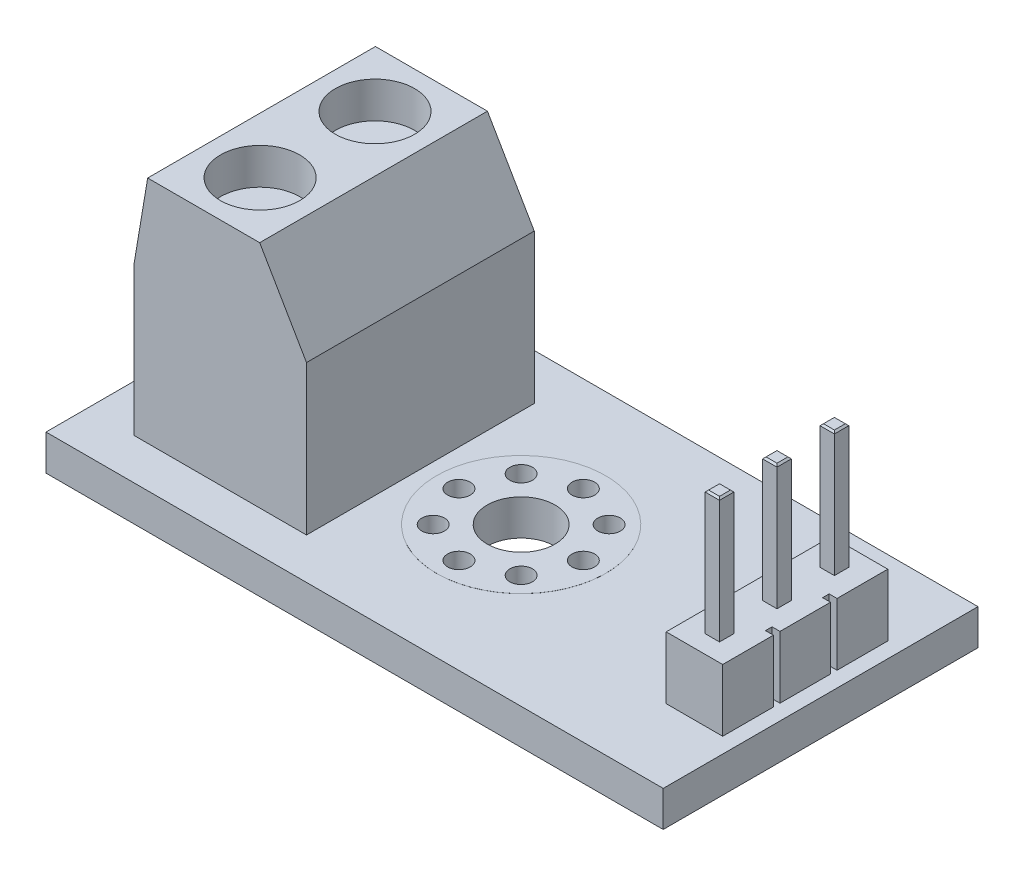
SolidWorks part; units mm, degrees
ref_plane "Front Plane" through (0, 0, 0) normal (0, 0, 1) x (1, 0, 0)
ref_plane "Top Plane" through (0, 0, 0) normal (0, 1, 0) x (1, 0, 0)
ref_plane "Right Plane" through (0, 0, 0) normal (1, 0, 0) x (0, 0, -1)
sketch "Sketch1" plane through (0, 0, 0) normal (0, 1, 0) x (1, 0, 0)
  line L1 (-13.6462, 6.9596) -> (13.6461, 6.9596)
  line L2 (-13.6462, 6.9596) -> (-13.6462, -6.9596)
  line L3 (-13.6462, -6.9596) -> (13.6461, -6.9596)
  line L4 (13.6461, 6.9596) -> (13.6461, -6.9596)
  line L5 (-13.6462, 6.9596) -> (13.6461, -6.9596) construction
  line L6 (-13.6462, -6.9596) -> (13.6461, 6.9596) construction
  point P0 (0, 0)
  dimension "D1" = 13.9192
  dimension "D2" = 27.2923
extrude "Boss-Extrude1" add sketch "Sketch1" along normal mid plane 1.5748
sketch "Sketch2" plane through (0, 0.7874, 0) normal (0, 1, 0) x (1, 0, 0)
  line L0 (-13.6462, 6.9596) -> (-13.6462, -6.9596) construction
  circle A2 centre (0.4038, 0) radius 1.5
  circle A3 centre (0.4038, 2.75) radius 0.5
  circle A5 centre (2.3484, 1.9445) radius 0.5
  circle A6 centre (3.1539, 0) radius 0.5
  circle A7 centre (2.3484, -1.9445) radius 0.5
  circle A8 centre (0.4039, -2.75) radius 0.5
  circle A9 centre (-1.5407, -1.9445) radius 0.5
  circle A10 centre (-2.3461, 0) radius 0.5
  circle A11 centre (-1.5407, 1.9445) radius 0.5
  point P24 (0.4039, 0)
  dimension "D1" = 3
  dimension "D2" = 12.55
  dimension "D3" = 2.75
  dimension "D4" = 1
  dimension "D5" = 8
extrude "Cut-Extrude1" cut sketch "Sketch2" against normal through all
sketch "Sketch3" plane through (0, 0.7874, 0) normal (0, 1, 0) x (1, 0, 0)
  line L0 (13.6461, -6.9596) -> (13.6461, 6.9596) construction
  line L1 (10.4661, 3.65) -> (12.9661, 3.65)
  line L2 (10.4661, 3.65) -> (10.4661, -3.65)
  line L3 (10.4661, -3.65) -> (12.9661, -3.65)
  line L4 (12.9661, 3.65) -> (12.9661, -3.65)
  line L5 (10.4661, 0) -> (12.9661, 0) construction
  dimension "D1" = 2.5
  dimension "D2" = 7.3
  dimension "D3" = 0.68
extrude "Boss-Extrude2" add sketch "Sketch3" along normal blind 2.75
sketch "Sketch4" plane through (0, 3.5374, 0) normal (0, 1, 0) x (1, 0, 0)
  line L0 (10.4661, 3.65) -> (10.4661, -3.65) construction
  line L1 (10.4661, 1.4064) -> (10.8161, 1.4064)
  line L2 (10.4661, 1.4064) -> (10.4661, 1.1164)
  line L3 (10.4661, 1.1164) -> (10.8161, 1.1164)
  line L4 (10.8161, 1.4064) -> (10.8161, 1.1164)
  line L5 (12.9661, 3.65) -> (10.4661, 3.65) construction
  line L6 (10.4661, -1.1164) -> (10.8161, -1.1164)
  line L7 (10.4661, -1.1164) -> (10.4661, -1.4064)
  line L8 (10.4661, -1.4064) -> (10.8161, -1.4064)
  line L9 (10.8161, -1.1164) -> (10.8161, -1.4064)
  line L14 (10.4661, -3.65) -> (12.9661, -3.65) construction
  line L15 (11.7161, 3.65) -> (11.7161, -3.65) construction
  line L16 (12.9661, 3.65) -> (10.4661, 3.65) construction
  line L17 (12.6161, -1.1164) -> (12.6161, -1.4064)
  line L18 (12.9661, -1.4064) -> (12.6161, -1.4064)
  line L19 (12.9661, -1.1164) -> (12.9661, -1.4064)
  line L20 (12.9661, -1.1164) -> (12.6161, -1.1164)
  line L21 (12.6161, 1.4064) -> (12.6161, 1.1164)
  line L22 (12.9661, 1.1164) -> (12.6161, 1.1164)
  line L23 (12.9661, 1.4064) -> (12.9661, 1.1164)
  line L24 (12.9661, 1.4064) -> (12.6161, 1.4064)
  dimension "D1" = 0.29
  dimension "D2" = 0.35
  dimension "D3" = 2.2436
  dimension "D4" = 2.2436
extrude "Cut-Extrude2" cut sketch "Sketch4" against normal up to surface (2.75 mm away) up to face at (0.4038, 0.7874, -2.25)
sketch "Sketch5" plane through (0, 3.5374, 0) normal (0, 1, 0) x (1, 0, 0)
  line L0 (11.7161, 3.65) -> (11.7161, -3.65) construction
  line L1 (12.9661, 3.65) -> (10.4661, 3.65) construction
  line L2 (10.4661, -3.65) -> (12.9661, -3.65) construction
  line L4 (11.3986, 0.3175) -> (12.0336, 0.3175)
  line L5 (11.3986, 0.3175) -> (11.3986, -0.3175)
  line L6 (11.3986, -0.3175) -> (12.0336, -0.3175)
  line L7 (12.0336, 0.3175) -> (12.0336, -0.3175)
  line L8 (11.3986, 0.3175) -> (12.0336, -0.3175) construction
  line L9 (11.3986, -0.3175) -> (12.0336, 0.3175) construction
  line L10 (11.3986, 2.8575) -> (12.0336, 2.8575)
  line L11 (11.3986, 2.8575) -> (11.3986, 2.2225)
  line L12 (11.3986, 2.2225) -> (12.0336, 2.2225)
  line L13 (12.0336, 2.8575) -> (12.0336, 2.2225)
  line L14 (11.3986, 2.8575) -> (12.0336, 2.2225) construction
  line L15 (11.3986, 2.2225) -> (12.0336, 2.8575) construction
  line L16 (11.3986, -2.2225) -> (12.0336, -2.2225)
  line L17 (11.3986, -2.2225) -> (11.3986, -2.8575)
  line L18 (11.3986, -2.8575) -> (12.0336, -2.8575)
  line L19 (12.0336, -2.2225) -> (12.0336, -2.8575)
  line L20 (11.3986, -2.2225) -> (12.0336, -2.8575) construction
  line L21 (11.3986, -2.8575) -> (12.0336, -2.2225) construction
  point P6 (11.7161, 0)
  point P11 (11.7161, 2.54)
  point P16 (11.7161, -2.54)
  dimension "D1" = 0.635
  dimension "D2" = 2.54
  dimension "D3" = 2.54
extrude "Boss-Extrude3" add sketch "Sketch5" along normal blind 5.5 and the other way offset from surface (5.7726 mm away) 1.4478 other way up to face at (0.4038, -0.7874, -2.25)
sketch "Sketch6" plane through (0, 0.7874, 0) normal (0, 1, 0) x (1, 0, 0)
  circle A0 centre (0.4038, 0) radius 3.7416
  circle A1 centre (-2.3461, 0) radius 0.5 construction
  circle A2 centre (-1.5407, -1.9445) radius 0.5 construction
  circle A3 centre (0.4039, -2.75) radius 0.5 construction
  circle A4 centre (2.3484, -1.9445) radius 0.5 construction
  circle A5 centre (3.1539, 0) radius 0.5 construction
  circle A6 centre (2.3484, 1.9445) radius 0.5 construction
  circle A7 centre (0.4038, 0) radius 1.5 construction
  circle A8 centre (-1.5407, 1.9445) radius 0.5 construction
  circle A9 centre (0.4038, 2.75) radius 0.5 construction
  circle A10 centre (-2.3461, 0) radius 0.5
  circle A11 centre (-1.5407, -1.9445) radius 0.5
  circle A12 centre (0.4039, -2.75) radius 0.5
  circle A13 centre (2.3484, -1.9445) radius 0.5
  circle A14 centre (3.1539, 0) radius 0.5
  circle A15 centre (2.3484, 1.9445) radius 0.5
  circle A16 centre (0.4038, 0) radius 1.5
  circle A17 centre (-1.5407, 1.9445) radius 0.5
  circle A18 centre (0.4038, 2.75) radius 0.5
extrude "Boss-Extrude4" add sketch "Sketch6" along normal blind 0.0025
mirror "Mirror1" about plane through (0, 0, 0) normal (0, 1, 0) of "Boss-Extrude4"
sketch "Sketch7" plane through (0, 0.7874, 0) normal (0, 1, 0) x (1, 0, 0)
  line L0 (-13.6462, 6.9596) -> (-13.6462, -6.9596) construction
  line L1 (-11.5634, 4.9276) -> (-3.9434, 4.9276)
  line L2 (-11.5634, 4.9276) -> (-11.5634, -5.1435)
  line L3 (-11.5634, -5.1435) -> (-3.9434, -5.1435)
  line L4 (-3.9434, 4.9276) -> (-3.9434, -5.1435)
  line L5 (13.6461, 6.9596) -> (-13.6462, 6.9596) construction
  dimension "D1" = 10.0711
  dimension "D2" = 7.62
  dimension "D3" = 2.0828
  dimension "D4" = 2.032
extrude "Boss-Extrude5" add sketch "Sketch7" along normal blind 10.16
sketch "Sketch8" plane through (0, 0, 0) normal (0, 0, 1) x (1, 0, 0)
  line L0 (-6.0135, 10.9474) -> (-3.9434, 7.3914)
  line L1 (-11.5634, 10.9474) -> (-3.9434, 10.9474) construction
  line L2 (-3.9434, 10.9474) -> (-3.9434, 0.7874) construction
  line L3 (-3.9434, 7.3914) -> (-3.9434, 10.9474)
  line L4 (-3.9434, 10.9474) -> (-6.0135, 10.9474)
  line L5 (-10.9665, 10.9474) -> (-11.5634, 10.9474)
  line L6 (-11.5634, 10.9474) -> (-11.5634, 7.3914)
  line L7 (-11.5634, 10.9474) -> (-11.5634, 0.7874) construction
  line L8 (-11.5634, 7.3914) -> (-10.9665, 10.9474)
  dimension "D1" = 4.953
  dimension "D2" = 2.0701
  dimension "D3" = 3.556
extrude "Cut-Extrude3" cut sketch "Sketch8" against normal through all both and the other way through all
sketch "Sketch9" plane through (0, 10.9474, 0) normal (0, 1, 0) x (1, 0, 0)
  line L0 (-10.9665, -0.1079) -> (-6.0135, -0.1079) construction
  line L1 (-10.9665, -5.1435) -> (-10.9665, 4.9276) construction
  line L2 (-6.0135, 4.9276) -> (-6.0135, -5.1435) construction
  circle A0 centre (-8.49, 2.4321) radius 1.7526
  circle A1 centre (-8.49, -2.6479) radius 1.7526
  point P12 (-8.49, -0.1079)
  dimension "D1" = 5.08
  dimension "D2" = 3.5052
extrude "Cut-Extrude4" cut sketch "Sketch9" against normal blind 1.6002
sketch "Sketch10" plane through (0, 0.7874, 0) normal (0, 1, 0) x (1, 0, 0)
  line L1 (-8.8075, 2.7496) -> (-8.1725, 2.7496)
  line L2 (-8.8075, 2.7496) -> (-8.8075, 2.1146)
  line L3 (-8.8075, 2.1146) -> (-8.1725, 2.1146)
  line L4 (-8.1725, 2.7496) -> (-8.1725, 2.1146)
  line L5 (-8.8075, 2.7496) -> (-8.1725, 2.1146) construction
  line L6 (-8.8075, 2.1146) -> (-8.1725, 2.7496) construction
  line L7 (-8.8075, -2.3304) -> (-8.1725, -2.3304)
  line L8 (-8.8075, -2.3304) -> (-8.8075, -2.9654)
  line L9 (-8.8075, -2.9654) -> (-8.1725, -2.9654)
  line L10 (-8.1725, -2.3304) -> (-8.1725, -2.9654)
  line L11 (-8.8075, -2.3304) -> (-8.1725, -2.9654) construction
  line L12 (-8.8075, -2.9654) -> (-8.1725, -2.3304) construction
  point P0 (-8.49, 2.4321)
  point P5 (-8.49, -2.6479)
  dimension "D1" = 0.635
extrude "Boss-Extrude6" add sketch "Sketch10" against normal offset from surface (3.7338 mm away) 2.159 up to face at (0.4038, -0.7874, 3.7416) offset beyond the face yes
chamfer "Chamfer1" distance 0.0762 angle 45 32 edges at (11.7161, 9.0374, -2.2225) (11.3986, 9.0374, -2.54) (11.7161, 9.0374, -2.8575) (12.0336, 9.0374, -2.54) (11.7161, 9.0374, 0.3175) (11.3986, 9.0374, 0) (11.7161, 9.0374, -0.3175) (12.0336, 9.0374, 0) (11.7161, 9.0374, 2.8575) (11.3986, 9.0374, 2.54) (11.7161, 9.0374, 2.2225) (12.0336, 9.0374, 2.54) (11.7161, -2.2352, -2.8575) (11.3986, -2.2352, -2.54) (11.7161, -2.2352, -2.2225) (12.0336, -2.2352, -2.54) (11.7161, -2.2352, -0.3175) (11.3986, -2.2352, 0) (11.7161, -2.2352, 0.3175) (12.0336, -2.2352, 0) (11.7161, -2.2352, 2.2225) (11.3986, -2.2352, 2.54) (11.7161, -2.2352, 2.8575) (12.0336, -2.2352, 2.54) (-8.49, -2.9464, 2.3304) (-8.8075, -2.9464, 2.6479) (-8.49, -2.9464, 2.9654) (-8.1725, -2.9464, 2.6479) (-8.49, -2.9464, -2.7496) (-8.8075, -2.9464, -2.4321) (-8.49, -2.9464, -2.1146) (-8.1725, -2.9464, -2.4321)
sketch "Sketch11" plane through (-11.5634, 0, 0) normal (-1, 0, 0) x (0, 0, 1)
  line L0 (0, 7.3914) -> (0, 0) construction
  line L1 (-4.4958, 6.5273) -> (-0.4318, 6.5273)
  line L2 (-4.4958, 6.5273) -> (-4.4958, 1.4473)
  line L3 (-4.4958, 1.4473) -> (-0.4318, 1.4473)
  line L4 (-0.4318, 6.5273) -> (-0.4318, 1.4473)
  line L5 (-4.9276, 7.3914) -> (5.1435, 7.3914) construction
  line L6 (4.4958, 1.4473) -> (0.4318, 1.4473)
  line L7 (0.4318, 6.5273) -> (0.4318, 1.4473)
  line L8 (4.4958, 6.5273) -> (0.4318, 6.5273)
  line L9 (4.4958, 6.5273) -> (4.4958, 1.4473)
  dimension "D1" = 5.08
  dimension "D2" = 4.064
  dimension "D3" = 0.8636
extrude "Cut-Extrude5" cut sketch "Sketch11" against normal blind 1.6002
